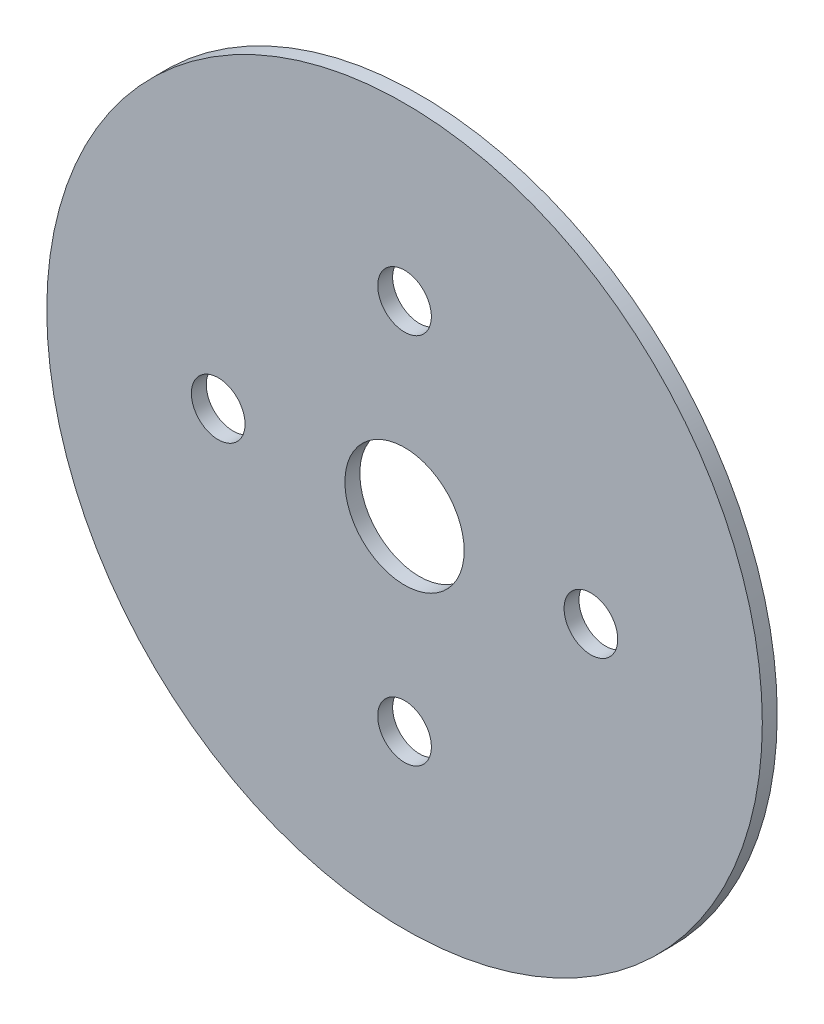
SolidWorks part; units mm, degrees
ref_plane "Front Plane" through (0, 0, 0) normal (0, 0, 1) x (1, 0, 0)
ref_plane "Top Plane" through (0, 0, 0) normal (0, 1, 0) x (1, 0, 0)
ref_plane "Right Plane" through (0, 0, 0) normal (1, 0, 0) x (0, 0, -1)
sketch "Sketch1" plane through (0, 0, 0) normal (0, 0, 1) x (1, 0, 0)
  circle A0 centre (0, 0) radius 30.48
  circle A1 centre (0, 0) radius 5.08
  circle A3 centre (0, 15.875) radius 2.286
  circle A4 centre (15.875, 0) radius 2.286
  circle A5 centre (0, -15.875) radius 2.286
  circle A6 centre (-15.875, 0) radius 2.286
  point P4 (0, 0)
  point P17 (0, 0)
  dimension "D1" = 4.572
  dimension "D2" = 10.16
  dimension "D4" = 60.96
  dimension "D3" = 15.875
extrude "Boss-Extrude1" add sketch "Sketch1" along normal blind 1.27
